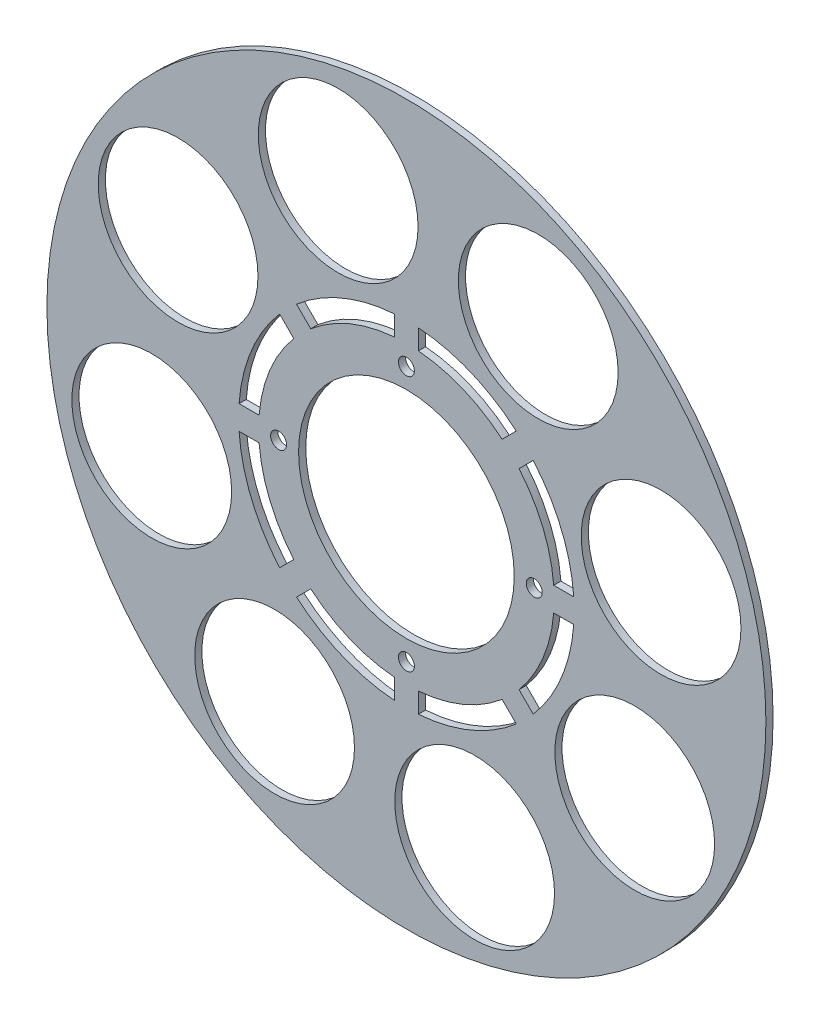
SolidWorks part; units mm, degrees
ref_plane "前视基准面" through (0, 0, 0) normal (0, 0, 1) x (1, 0, 0)
ref_plane "上视基准面" through (0, 0, 0) normal (0, 1, 0) x (1, 0, 0)
ref_plane "右视基准面" through (0, 0, 0) normal (1, 0, 0) x (0, 0, -1)
sketch "草图1" plane through (0, 0, 0) normal (0, 0, 1) x (1, 0, 0)
  circle A1 centre (-32, 0) radius 2
  circle A2 centre (0, 32) radius 2
  circle A3 centre (32, 0) radius 2
  circle A4 centre (0, -32) radius 2
  circle A5 centre (0, 0) radius 27
  circle A6 centre (0, 0) radius 37
  point P14 (0, 0)
  dimension "D2" = 4
  dimension "D3" = 4
extrude "凸台-拉伸1" add sketch "草图1" along normal blind 3
sketch "草图2" plane through (0, 0, 3) normal (0, 0, 1) x (1, 0, 0)
  line L0 (0, 0) -> (-66, 0)
  line L1 (0, 0) -> (-63.7511, -17.0821)
  circle A0 centre (0, 0) radius 66
  circle A1 centre (-63.7511, -17.0821) radius 20
  circle A2 centre (-17.0821, 63.7511) radius 20
  circle A3 centre (63.7511, 17.0821) radius 20
  circle A4 centre (17.0821, -63.7511) radius 20
  circle A5 centre (0, 0) radius 42
  circle A6 centre (0, 0) radius 90
  point P15 (0, 0)
  dimension "D1" = 15
  dimension "D2" = 4
extrude "凸台-拉伸2" add sketch "草图2" against normal blind 3 separate body contours A5 L0 A1 L1 | A5 L1 A1 A0 A4 A3 A2 L0 | A6 A4 A0 A1 A2 A3
sketch "草图3" plane through (0, 0, 3) normal (0, 0, 1) x (1, 0, 0)
  line L0 (-37, 0) -> (-42, 0)
  line L1 (-37, 3) -> (-37, -3)
  line L2 (-41.8927, 3) -> (-34.0606, 3)
  line L3 (-34.0606, 3) -> (-34.0606, -3)
  line L4 (-34.0606, -3) -> (-43.2048, -3)
  line L5 (-43.2048, -3) -> (-43.2048, 3)
  line L6 (-43.2048, 3) -> (-41.8927, 3)
  line L7 (-28.4291, 32.6717) -> (-27.5013, 31.7439)
  line L8 (-27.5013, 31.7439) -> (-21.9631, 26.2058)
  line L9 (-21.9631, 26.2058) -> (-26.2058, 21.9631)
  line L10 (-26.2058, 21.9631) -> (-32.6717, 28.4291)
  line L11 (-32.6717, 28.4291) -> (-28.4291, 32.6717)
  line L12 (3, 43.2048) -> (3, 41.8927)
  line L13 (3, 41.8927) -> (3, 34.0606)
  line L14 (3, 34.0606) -> (-3, 34.0606)
  line L15 (-3, 34.0606) -> (-3, 43.2048)
  line L16 (-3, 43.2048) -> (3, 43.2048)
  line L17 (32.6717, 28.4291) -> (31.7439, 27.5013)
  line L18 (31.7439, 27.5013) -> (26.2058, 21.9631)
  line L19 (26.2058, 21.9631) -> (21.9631, 26.2058)
  line L20 (21.9631, 26.2058) -> (28.4291, 32.6717)
  line L21 (28.4291, 32.6717) -> (32.6717, 28.4291)
  line L22 (43.2048, -3) -> (41.8927, -3)
  line L23 (41.8927, -3) -> (34.0606, -3)
  line L24 (34.0606, -3) -> (34.0606, 3)
  line L25 (34.0606, 3) -> (43.2048, 3)
  line L26 (43.2048, 3) -> (43.2048, -3)
  line L27 (28.4291, -32.6717) -> (27.5013, -31.7439)
  line L28 (27.5013, -31.7439) -> (21.9631, -26.2058)
  line L29 (21.9631, -26.2058) -> (26.2058, -21.9631)
  line L30 (26.2058, -21.9631) -> (32.6717, -28.4291)
  line L31 (32.6717, -28.4291) -> (28.4291, -32.6717)
  line L32 (-3, -43.2048) -> (-3, -41.8927)
  line L33 (-3, -41.8927) -> (-3, -34.0606)
  line L34 (-3, -34.0606) -> (3, -34.0606)
  line L35 (3, -34.0606) -> (3, -43.2048)
  line L36 (3, -43.2048) -> (-3, -43.2048)
  line L37 (-32.6717, -28.4291) -> (-31.7439, -27.5013)
  line L38 (-31.7439, -27.5013) -> (-26.2058, -21.9631)
  line L39 (-26.2058, -21.9631) -> (-21.9631, -26.2058)
  line L40 (-21.9631, -26.2058) -> (-28.4291, -32.6717)
  line L41 (-28.4291, -32.6717) -> (-32.6717, -28.4291)
  circle A0 centre (0, 0) radius 37 construction
  circle A1 centre (0, 0) radius 42 construction
  point P10 (-37, 0)
  point P53 (0, 0)
  dimension "D1" = 6
  dimension "D2" = 8
extrude "凸台-拉伸3" add sketch "草图3" against normal blind 3 contours L10 L11 L7 L8 L9 | L15 L16 L12 L13 L14 | L18 L19 L20 L21 L17 | L23 L24 L25 L26 L22 | L28 L29 L30 L31 L27 | L35 L36 L32 L33 L34 | L40 L41 L37 L38 L39 | L4 L5 L6 L2 L3
sketch "草图5" plane through (0, 0, 3) normal (0, 0, 1) x (1, 0, 0)
  line L0 (0, 0) -> (-63.7511, -17.0821)
  line L1 (0, 0) -> (-57.1577, 33)
  circle A0 centre (0, 0) radius 66
  circle A1 centre (-57.1577, 33) radius 20
  circle A2 centre (33, 57.1577) radius 20
  circle A3 centre (57.1577, -33) radius 20
  circle A4 centre (-33, -57.1577) radius 20
  dimension "D2" = 4
  dimension "D1" = 45
extrude "切除-拉伸1" cut sketch "草图5" against normal through all both and the other way through all contours A1 | A2 | A3 | A4
sketch "草图6" plane through (0, 0, 0) normal (0, 1, 0) x (1, 0, 0)
  line L4 (100.3741, 28.2258) -> (-90, 7.3692)
  line L5 (-90, 0) -> (-90, 7.3692)
  line L6 (-90, 0) -> (-90, -1.2)
  line L7 (-90, 0) -> (-90, -3) construction
  line L8 (-90, -1.2) -> (96.1955, -1.2)
  line L9 (96.1955, -1.2) -> (100.3741, 28.2258)
  dimension "D1" = 1.2
extrude "切除-拉伸2" cut sketch "草图6" against normal through all both and the other way through all contours L4 L5 L6 L8 L9
